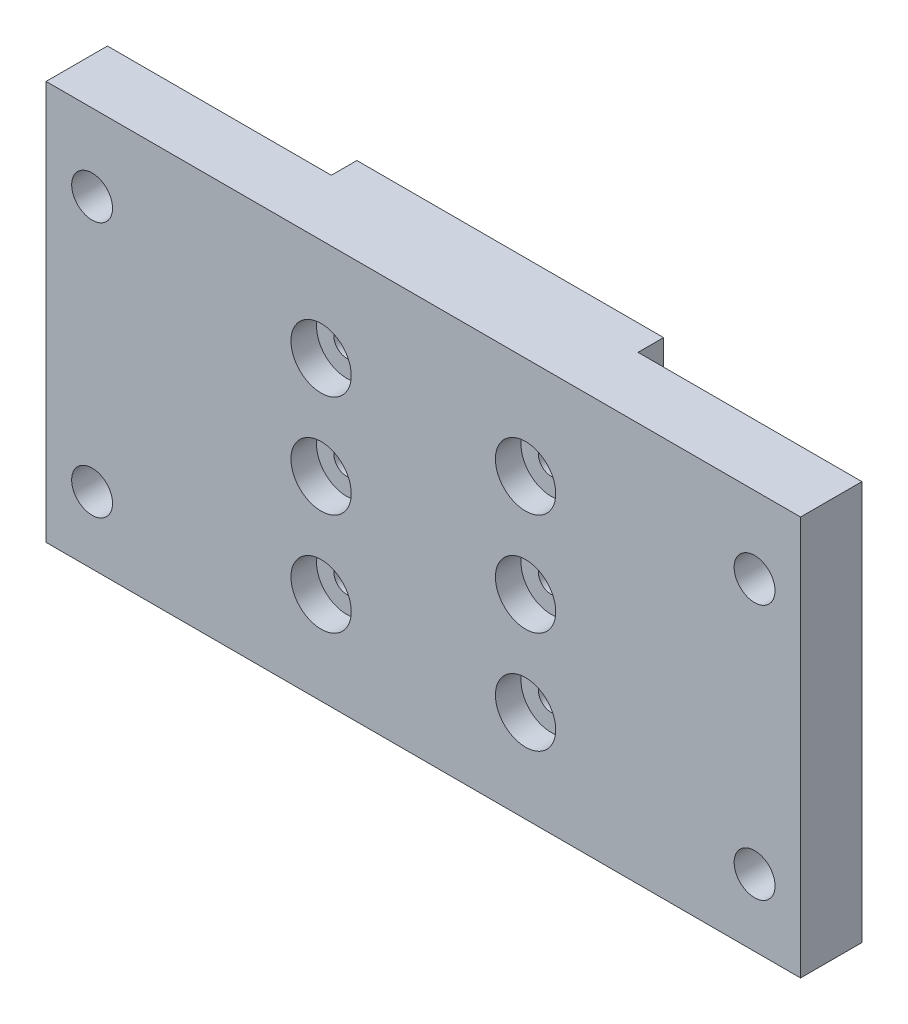
SolidWorks part; units mm, degrees
ref_plane "Front Plane" through (0, 0, 0) normal (0, 0, 1) x (1, 0, 0)
ref_plane "Top Plane" through (0, 0, 0) normal (0, 1, 0) x (1, 0, 0)
ref_plane "Right Plane" through (0, 0, 0) normal (1, 0, 0) x (0, 0, -1)
sketch "Sketch1" plane through (0, 0, 0) normal (0, 0, 1) x (1, 0, 0)
  line L1 (-73.8, -39.05) -> (73.8, -39.05)
  line L2 (-73.8, -39.05) -> (-73.8, 39.05)
  line L3 (-73.8, 39.05) -> (73.8, 39.05)
  line L4 (73.8, -39.05) -> (73.8, 39.05)
  line L5 (-73.8, -39.05) -> (73.8, 39.05) construction
  line L6 (-73.8, 39.05) -> (73.8, -39.05) construction
  point P0 (0, 0)
  dimension "D1" = 147.6
  dimension "D2" = 78.1
extrude "Boss-Extrude1" add sketch "Sketch1" along normal blind 12
sketch "Sketch2" plane through (0, 0, 0) normal (0, 0, -1) x (-1, 0, 0)
  line L0 (0, 39.05) -> (0, -39.05) construction
  line L1 (-73.8, 39.05) -> (73.8, 39.05) construction
  line L2 (73.8, -39.05) -> (-73.8, -39.05) construction
  line L4 (-30, 39.05) -> (30, 39.05)
  line L5 (-30, 39.05) -> (-30, -39.05)
  line L6 (-30, -39.05) -> (30, -39.05)
  line L7 (30, 39.05) -> (30, -39.05)
  point P10 (0, 39.05)
  dimension "D1" = 60
extrude "Boss-Extrude2" add sketch "Sketch2" along normal blind 5
sketch "Sketch3" plane through (0, 0, -5) normal (0, 0, -1) x (-1, 0, 0)
  line L0 (0, 39.05) -> (0, -39.05) construction
  line L1 (30, 39.05) -> (-30, 39.05) construction
  line L2 (-30, -39.05) -> (30, -39.05) construction
  line L3 (-20, 39.05) -> (-20, -39.05) construction
  circle A0 centre (-20, 19.05) radius 2.5
  circle A1 centre (-20, -0.95) radius 2.5
  circle A2 centre (-20, -20.95) radius 2.5
  circle A3 centre (20, -20.95) radius 2.5
  circle A4 centre (20, -0.95) radius 2.5
  circle A5 centre (20, 19.05) radius 2.5
  dimension "D2" = 5
  dimension "D1" = 20
  dimension "D3" = 20
  dimension "D4" = 20
  dimension "D5" = 20
extrude "Cut-Extrude1" cut sketch "Sketch3" against normal through all
sketch "Sketch4" plane through (0, 0, 12) normal (0, 0, 1) x (1, 0, 0)
  line L0 (0, 39.05) -> (0, -39.05) construction
  line L1 (73.8, 39.05) -> (-73.8, 39.05) construction
  line L2 (-73.8, -39.05) -> (73.8, -39.05) construction
  line L3 (64.8, 39.05) -> (64.8, -39.05) construction
  line L4 (73.8, -39.05) -> (73.8, 39.05) construction
  circle A0 centre (64.8, 24.05) radius 4
  circle A1 centre (64.8, -25.95) radius 4
  circle A2 centre (-64.8, -25.95) radius 4
  circle A3 centre (-64.8, 24.05) radius 4
  dimension "D1" = 8
  dimension "D2" = 50
  dimension "D3" = 9
  dimension "D4" = 15
extrude "Cut-Extrude2" cut sketch "Sketch4" against normal through all
sketch "Sketch5" plane through (0, 0, 12) normal (0, 0, 1) x (1, 0, 0)
  circle A0 centre (-20, 19.05) radius 5.9
  circle A1 centre (20, 19.05) radius 5.9
  circle A2 centre (-20, -0.95) radius 5.9
  circle A3 centre (20, -0.95) radius 5.9
  circle A4 centre (-20, -20.95) radius 5.9
  circle A5 centre (20, -20.95) radius 5.9
  dimension "D1" = 11.8
extrude "Cut-Extrude3" cut sketch "Sketch5" against normal blind 5
sketch "Sketch6" plane through (0, 0, 12) normal (0, 0, 1) x (1, 0, 0)
  line L0 (-14.1, 19.05) -> (-25.9, 19.05) construction
  circle A0 centre (-20, 19.05) radius 5.9 construction
  point P5 (-20, 19.05)
